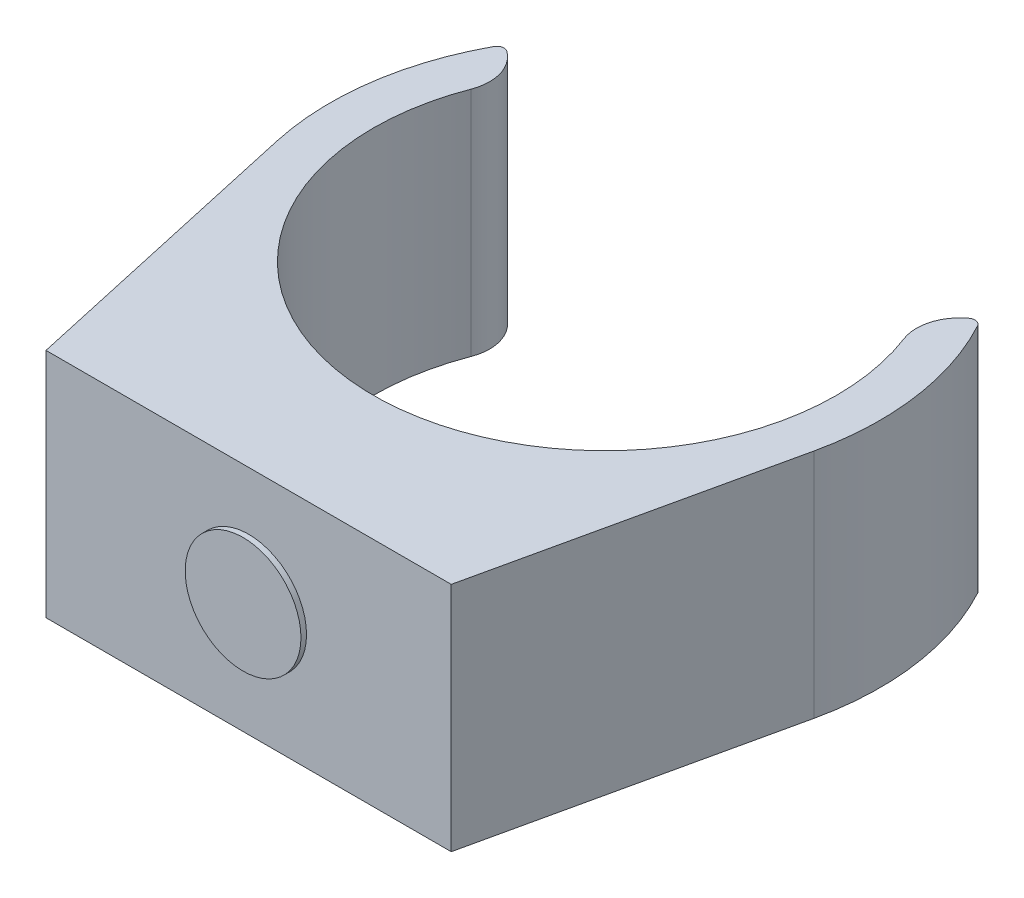
SolidWorks part; units mm, degrees
ref_plane "Alzado" through (0, 0, 0) normal (0, 0, 1) x (1, 0, 0)
ref_plane "Planta" through (0, 0, 0) normal (0, 1, 0) x (1, 0, 0)
ref_plane "Vista lateral" through (0, 0, 0) normal (1, 0, 0) x (0, 0, -1)
sketch "Croquis1" plane through (0, 0, 0) normal (0, 1, 0) x (1, 0, 0)
  line L0 (0, 0) -> (0, 40) construction
  line L1 (0, 0) -> (16.4545, 9.5)
  line L2 (0, 0) -> (-16.4545, 9.5)
  arc A0 (-16.4545, 9.5) -> (16.4545, 9.5) centre (0, 0) ccw
  arc A1 (-13.8564, 8) -> (13.8564, 8) centre (0, 0) ccw
  circle A3 centre (0, 0) radius 16 construction
  circle A4 centre (0, 0) radius 19 construction
  point P3 (38.2522, 11.6949)
  point P8 (37, 0)
  dimension "D1" = 38
  dimension "D3" = 60
  dimension "D2" = 3
extrude "Extruir1" add sketch "Croquis1" along normal blind 16 contours A1 L2 A0 L1
sketch "Croquis2" plane through (0, 0, 0) normal (0, 0, 1) x (1, 0, 0)
  line L0 (0, 0) -> (0, 16) construction
  line L1 (19, 16) -> (-19, 16) construction
  circle A0 centre (0, 8) radius 4
  dimension "D1" = 8
extrude "Extruir2" add sketch "Croquis2" against normal up to surface (6.4258 mm away) from offset 25
fillet "Redondeo1" radius 3 2 edges at (-13.8564, 8, -8) (13.8564, 8, -8)
fillet "Redondeo2" radius 0.5 2 edges at (16.4545, 8, -9.5) (-16.4545, 8, -9.5)
sketch "Croquis3" plane through (0, 16, 0) normal (0, 1, 0) x (1, 0, 0)
  line L0 (-18.5488, -4.1159) -> (-14, -24.6159)
  line L1 (-14, -24.6159) -> (14, -24.6159)
  line L2 (-18.5488, -4.1159) -> (-15.4615, -4.1159)
  line L3 (0, -24.6159) -> (0, -16) construction
  line L4 (18.5488, -4.1159) -> (14, -24.6159)
  line L5 (18.5488, -4.1159) -> (15.4615, -4.1159)
  arc A0 (-16.7123, 9.0387) -> (16.7123, 9.0387) centre (0, 0) ccw construction
  arc A1 (-14.9457, 5.7118) -> (14.9457, 5.7118) centre (0, 0) ccw construction
  arc A2 (-15.4615, -4.1159) -> (15.4615, -4.1159) centre (0, 0) ccw
  dimension "D1" = 14
  dimension "D2" = 20.5
extrude "Extruir3" add sketch "Croquis3" against normal up to surface (16 mm away) up to face at (0, 0, 0.1929)
